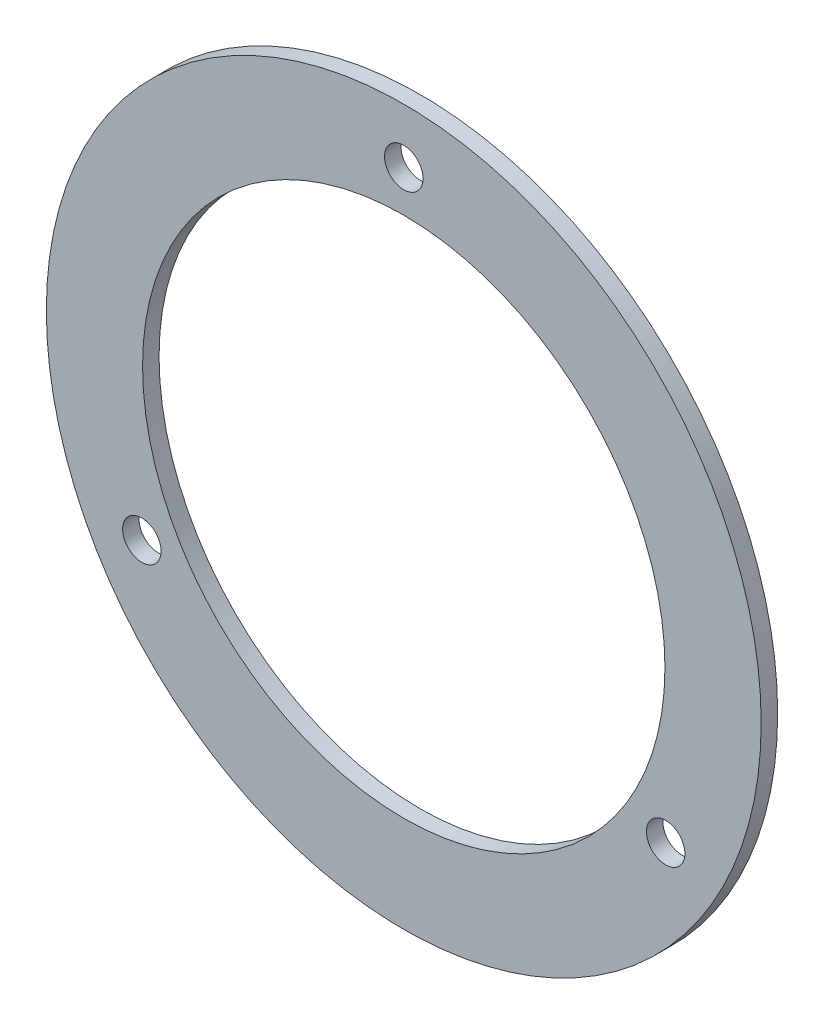
SolidWorks part; units mm, degrees
material "ASTM A36 Steel"
ref_plane "Front Plane" through (0, 0, 0) normal (0, 0, 1) x (1, 0, 0)
ref_plane "Top Plane" through (0, 0, 0) normal (0, 1, 0) x (1, 0, 0)
ref_plane "Right Plane" through (0, 0, 0) normal (1, 0, 0) x (0, 0, -1)
sketch "Sketch1" plane through (0, 0, 0) normal (0, 0, 1) x (1, 0, 0)
  circle A0 centre (0, 0) radius 47.5
  circle A1 centre (0, 0) radius 65
  dimension "D1" = 95
  dimension "D2" = 130
extrude "Boss-Extrude1" add sketch "Sketch1" along normal blind 3
sketch "Sketch2" plane through (0, 0, 3) normal (0, 0, 1) x (1, 0, 0)
  circle A1 centre (0, 55) radius 3.5
  dimension "D1" = 55
  dimension "D2" = 7
extrude "Cut-Extrude1" cut sketch "Sketch2" against normal blind 3
pattern_circular "CirPattern1" count 3 over 360 about axis through (0, 0, 0) along (0, 0, 1) of "Cut-Extrude1"
